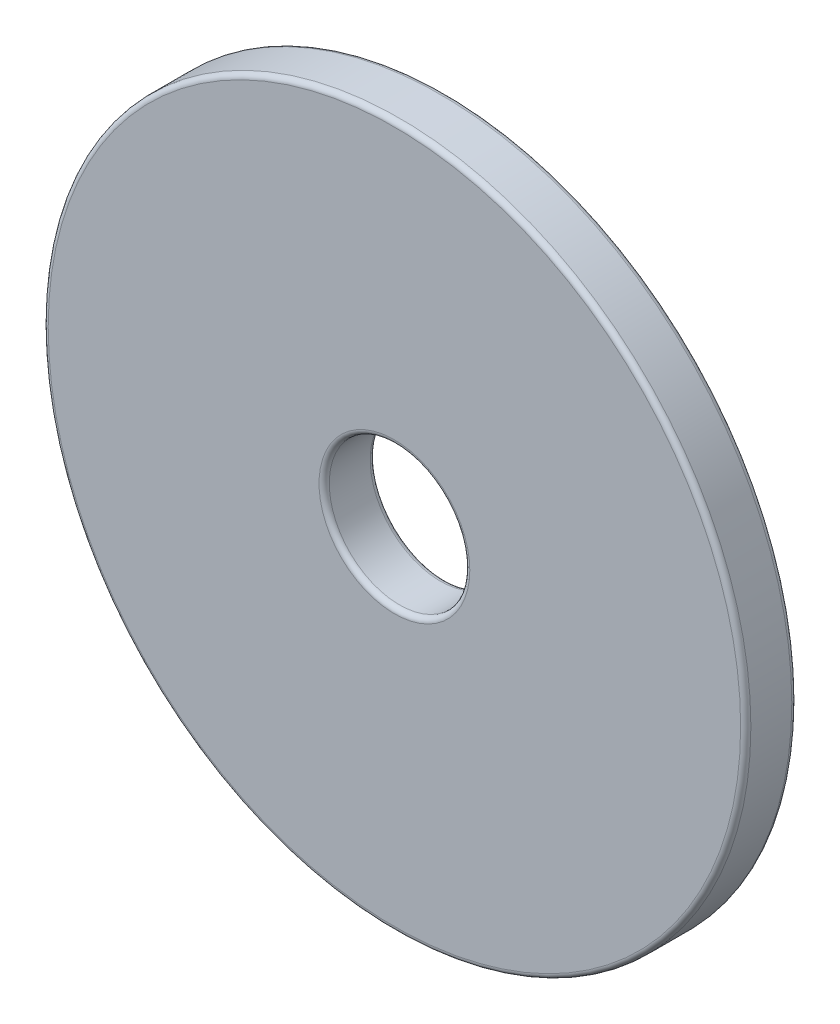
SolidWorks part; units mm, degrees
ref_plane "Front Plane" through (0, 0, 0) normal (0, 0, 1) x (1, 0, 0)
ref_plane "Top Plane" through (0, 0, 0) normal (0, 1, 0) x (1, 0, 0)
ref_plane "Right Plane" through (0, 0, 0) normal (1, 0, 0) x (0, 0, -1)
sketch "Sketch1" plane through (0, 0, 0) normal (0, 0, 1) x (1, 0, 0)
  circle A0 centre (0, 0) radius 1.5875
  circle A1 centre (0, 0) radius 7.9375
  point P4 (0, 7.9375)
  point P5 (0, 1.5875)
  point P6 (0, -1.5875)
  point P7 (1.5875, 0)
  point P8 (-1.5875, 0)
  dimension "OD" = 15.875
  dimension "ID" = 3.175
sketch "Sketch2" plane through (0, 0, 0) normal (1, 0, 0) x (0, 0, -1)
  line L1 (-0.5778, 7.9375) -> (0.5778, 7.9375)
  line L2 (-0.5778, 7.9375) -> (-0.5778, -7.9375)
  line L3 (-0.5778, -7.9375) -> (0.5778, -7.9375)
  line L4 (0.5778, 7.9375) -> (0.5778, -7.9375)
  point P4 (0, 7.9375)
  point P5 (0.5779, 0)
  dimension "Thickness Range" = 1.1557
sketch "Sketch3" plane through (0, 0, 0) normal (0, 0, 1) x (1, 0, 0)
  circle A0 centre (0, 0) radius 1.5875 construction
  circle A1 centre (0, 0) radius 7.9375 construction
  circle A2 centre (0, 0) radius 1.5875
  circle A3 centre (0, 0) radius 7.9375
extrude "Boss-Extrude1" add sketch "Sketch3" against normal up to vertex (0.5778 mm away) from vertex at 0.5778 starting at point (0, 7.9375, 0.5778)
fillet "Fillet1" radius 0.1156 4 edges at (1.5875, 0, 0.5778) (1.5875, 0, -0.5778) (7.9375, 0, 0.5778) (7.9375, 0, -0.5778)
equation "\"D1@Fillet1\"=\"Thickness Range@Sketch2\"*.1"
